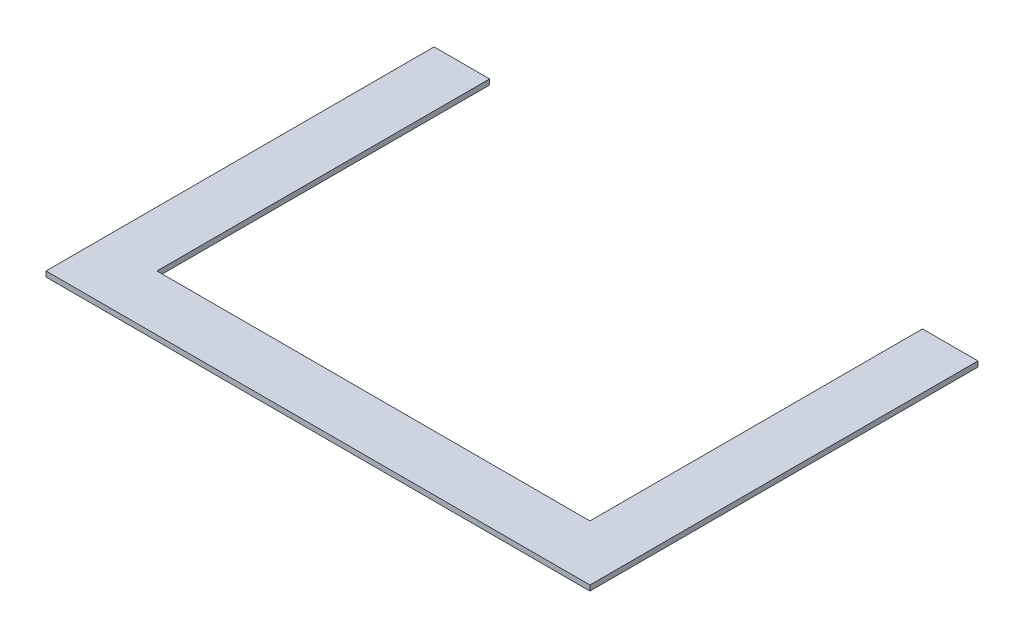
SolidWorks part; units mm, degrees
ref_plane "Front Plane" through (0, 0, 0) normal (0, 0, 1) x (1, 0, 0)
ref_plane "Top Plane" through (0, 0, 0) normal (0, 1, 0) x (1, 0, 0)
ref_plane "Right Plane" through (0, 0, 0) normal (1, 0, 0) x (0, 0, -1)
sketch "Sketch1" plane through (0, 0, 0) normal (0, 1, 0) x (1, 0, 0)
  line L0 (-40.5009, 36.7672) -> (-21.3493, 36.7672)
  line L1 (-21.3493, 36.7672) -> (-21.3493, -78.0281)
  line L2 (-21.3493, -78.0281) -> (128.0789, -78.0281)
  line L3 (128.0789, -78.0281) -> (128.0789, 36.7672)
  line L4 (128.0789, 36.7672) -> (147.2305, 36.7672)
  line L5 (147.2305, 36.7672) -> (147.2305, -97.1797)
  line L6 (147.2305, -97.1797) -> (-40.5009, -97.1797)
  line L7 (-40.5009, -97.1797) -> (-40.5009, 36.7672)
  dimension "D1" = 19.1516
  dimension "D2" = 19.1516
  dimension "D3" = 187.7314
  dimension "D4" = 149.4282
  dimension "D5" = 133.9469
  dimension "D6" = 133.9469
  dimension "D7" = 114.7953
  dimension "D8" = 114.7953
  dimension "D9" = 19.1516
extrude "Boss-Extrude1" add sketch "Sketch1" along normal blind 1.8288
